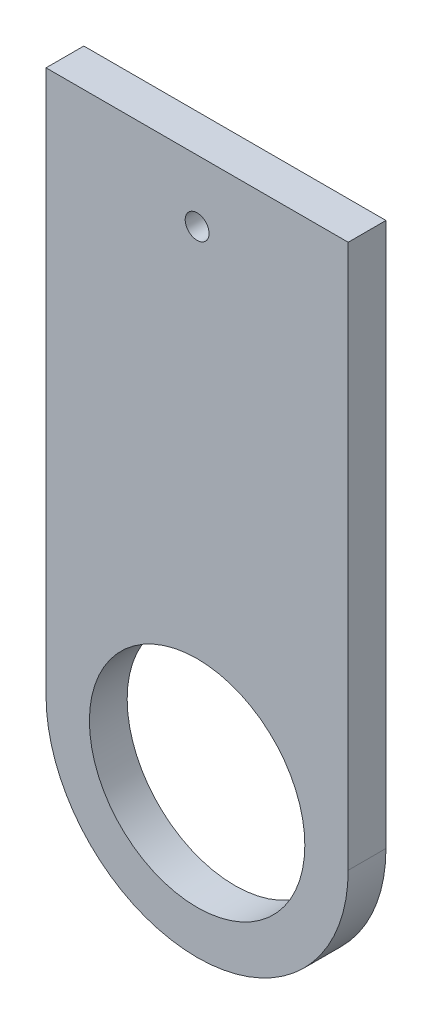
SolidWorks part; units mm, degrees
ref_plane "Front Plane" through (0, 0, 0) normal (0, 0, 1) x (1, 0, 0)
ref_plane "Top Plane" through (0, 0, 0) normal (0, 1, 0) x (1, 0, 0)
ref_plane "Right Plane" through (0, 0, 0) normal (1, 0, 0) x (0, 0, -1)
sketch "Sketch1" plane through (0, 0, 0) normal (0, 0, 1) x (1, 0, 0)
  line L0 (0, 78.0535) -> (0, -76.7078) construction
  line L1 (-108.1983, 0.6729) -> (119.7718, 0.6729) construction
  line L2 (-12.0732, -76.7078) -> (17.2347, -76.7078) construction
  line L3 (-20, -76.7078) -> (-20, -58.5041)
  line L4 (-20, -4.7078) -> (20, -4.7078)
  line L5 (20, -4.7078) -> (20, -76.7078)
  line L9 (-20, -4.7078) -> (-20, -58.5041)
  line L10 (-38, -22.9117) -> (-38, -2.9117) construction
  arc A0 (-20, -76.7078) -> (20, -76.7078) centre (0, -76.7078) ccw
  circle A3 centre (0, -12.9117) radius 1.58
  circle A4 centre (0, -76.7078) radius 14.26
  dimension "D1" = 40
  dimension "D4" = 20
  dimension "D5" = 3.16
  dimension "D2" = 40
  dimension "D3" = 72
extrude "Boss-Extrude1" add sketch "Sketch1" along normal blind 5
